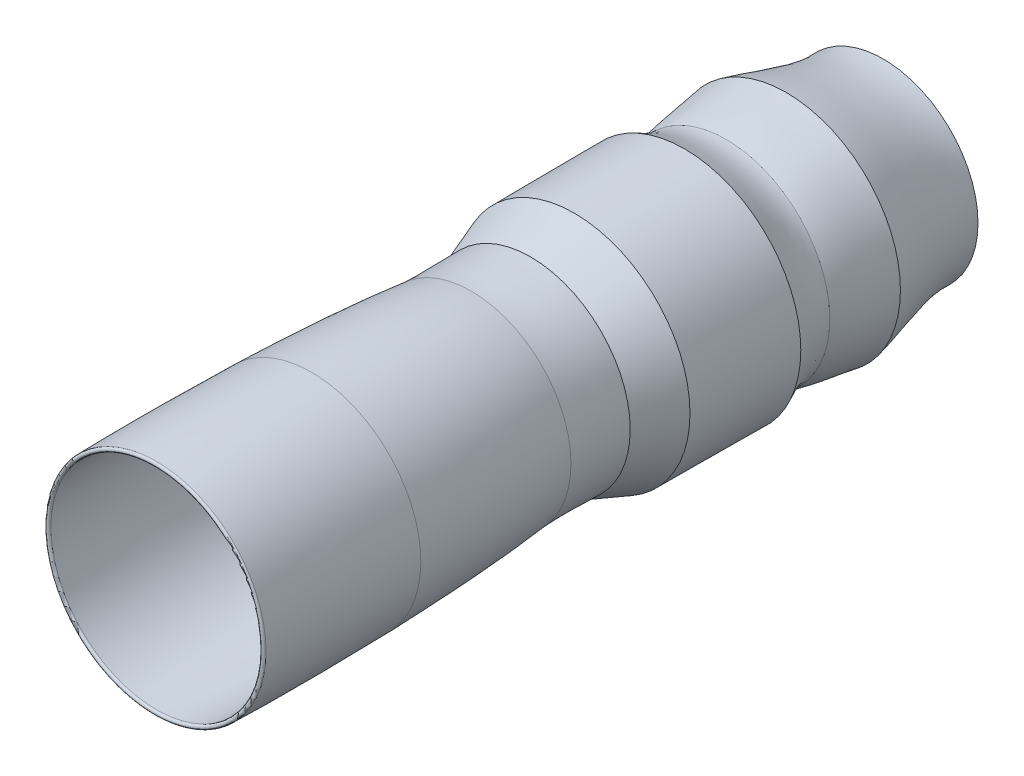
SolidWorks part; units mm, degrees
ref_plane "Front Plane" through (0, 0, 0) normal (0, 0, 1) x (1, 0, 0)
ref_plane "Top Plane" through (0, 0, 0) normal (0, 1, 0) x (1, 0, 0)
ref_plane "Right Plane" through (0, 0, 0) normal (1, 0, 0) x (0, 0, -1)
sketch "Sketch8" plane through (0, 0, 0) normal (1, 0, 0) x (0, 0, -1)
  line L0 (0, 0) -> (5590, 0) construction
  line L1 (0, 0) -> (5607.581, 0)
  line L2 (375.2101, 261.6749) -> (557.709, 261.6749)
  line L3 (557.709, 261.6749) -> (557.709, 0)
  line L4 (557.709, 0) -> (0, 0)
  spline S0 degree 2 poles (0, 0) (27.9707, 205.406) (375.2101, 261.6749) knots 0 0 0 1 1 1
  dimension "D1" = 5590
sketch "Sketch9" plane through (0, 0, 0) normal (1, 0, 0) x (0, 0, -1)
  line L0 (0, 0) -> (5607.581, 0) construction
  line L1 (557.709, 261.6749) -> (557.709, 0) construction
  line L2 (375.2101, 261.6749) -> (557.709, 261.6749) construction
  line L3 (0, 0) -> (5607.581, 0)
  line L4 (557.709, 261.6749) -> (557.709, 0)
  line L5 (375.2101, 261.6749) -> (557.709, 261.6749)
  line L6 (557.709, 0) -> (0, 0)
  parabola Q0 (0, 0) -> (375.2101, 261.6749) focus (120.2694, 20.1897) apex (19.5309, 67.2468) construction
  parabola Q1 (0, 0) -> (375.2101, 261.6749) focus (120.2694, 20.1897) apex (19.5309, 67.2468)
  point P7 (466.4596, 0)
  dimension "D1" = 261.6749
  dimension "D2" = 182.4989
sketch "Sketch11" plane through (0, 0, 0) normal (1, 0, 0) x (0, 0, -1)
  line L0 (557.709, 231.1749) -> (607.709, 231.1749)
  line L1 (557.709, 261.6749) -> (557.709, 0) construction
  line L2 (607.709, 231.1749) -> (607.709, 0)
  line L3 (0, 0) -> (5607.581, 0) construction
  line L5 (375.2101, 261.6749) -> (557.709, 261.6749) construction
  line L7 (607.709, 0) -> (557.709, 0)
  line L8 (557.709, 231.1749) -> (557.709, 0)
  dimension "D2" = 30.5
sketch "Sketch57" plane through (0, 0, 0) normal (1, 0, 0) x (0, 0, -1)
  line L1 (5548.1816, 676.7722) -> (5549.9439, 646.824)
  arc A1 (355.6183, 783.4894) -> (356.1612, 753.4943) centre (355.8897, 768.4918) ccw
  spline S0 degree 3 poles (356.1612, 753.4943) (725.1108, 760.1721) (1094.102, 758.4341) (1463.1876, 750.663) knots 0 0 0 0 1 1 1 1
  spline S1 degree 3 poles (1463.1876, 750.663) (1843.519, 737.2017) (2224.4299, 724.6791) (2602.8221, 681.8746) knots 0 0 0 0 1 1 1 1
  spline S2 degree 3 poles (2602.8221, 681.8746) (2746.451, 673.1497) (2890.1052, 679.394) (3034.5032, 681.7486) knots 0 0 0 0 1 1 1 1
  spline S3 degree 1 poles (3034.5032, 681.7486) (3347.188, 795.7739) knots 0 0 1 1
  spline S4 degree 1 poles (3347.188, 795.7739) (4122.347, 800.0453) knots 0 0 1 1
  spline S5 degree 3 poles (4122.347, 800.0453) (4218.8819, 754.2521) (4321.2413, 701.1376) (4430.393, 711.435) knots 0 0 0 0 1 1 1 1
  spline S6 degree 3 poles (4430.393, 711.435) (4568.687, 749.5665) (4711.6907, 760.5752) (4854.4305, 784.957) knots 0 0 0 0 1 1 1 1
  spline S7 degree 3 poles (4854.4305, 784.957) (5084.739, 731.7888) (5313.7621, 632.9255) (5549.9439, 646.824) knots 0 0 0 0 1 1 1 1
  spline S8 degree 1 poles (355.6183, 783.4894) (1464.034, 780.6519) knots 0 0 1 1 construction
  spline S9 degree 1 poles (1464.034, 780.6519) (2605.4158, 711.7724) knots 0 0 1 1 construction
  spline S10 degree 1 poles (2605.4158, 711.7724) (3028.9628, 711.6607) knots 0 0 1 1 construction
  spline S11 degree 1 poles (3028.9628, 711.6607) (3341.8087, 825.7447) knots 0 0 1 1 construction
  spline S12 degree 1 poles (3341.8087, 825.7447) (4129.0233, 830.0826) knots 0 0 1 1 construction
  spline S13 degree 1 poles (4129.0233, 830.0826) (4425.0429, 741.076) knots 0 0 1 1 construction
  spline S14 degree 1 poles (4425.0429, 741.076) (4855.3132, 815.5423) knots 0 0 1 1 construction
  spline S15 degree 1 poles (4855.3132, 815.5423) (5548.1816, 676.7722) knots 0 0 1 1 construction
  spline S16 degree 3 poles (355.6183, 783.4894) (447.9786, 785.1611) (632.7273, 787.4512) (909.8236, 787.9485) (1186.9212, 785.7337) (1371.672, 782.5965) (1464.034, 780.6519) knots 0 0 0 0 0.250049 0.500097 0.750146 1.000194 1.000194 1.000194 1.000194
  spline S17 degree 3 poles (1464.034, 780.6519) (1511.5656, 778.9695) (1606.6034, 775.6358) (1796.8781, 768.5929) (2034.844, 758.176) (2272.7713, 743.1606) (2439.1709, 728.9467) (2534.1886, 719.5826) (2581.6852, 714.4543) (2605.4158, 711.7724) knots -0.000188 -0.000188 -0.000188 -0.000188 0.12475 0.249688 0.499564 0.749441 0.874379 0.936848 0.999317 0.999317 0.999317 0.999317
  spline S18 degree 3 poles (2605.4158, 711.7724) (2622.8817, 710.7181) (2657.8227, 709.0567) (2727.908, 707.2414) (2798.2607, 707.2814) (2868.927, 708.3467) (2922.088, 709.4485) (2966.5344, 710.4436) (3002.1731, 711.1794) (3020.0363, 711.5097) (3028.9628, 711.6607) knots 0.001824 0.001824 0.001824 0.001824 0.125144 0.248463 0.495103 0.618422 0.741742 0.865061 0.926721 0.988381 0.988381 0.988381 0.988381
  spline S19 degree 1 poles (3028.9628, 711.6607) (3341.8087, 825.7447) knots 0.015151 0.015151 1.015666 1.015666
  spline S20 degree 1 poles (3341.8087, 825.7447) (4129.0233, 830.0826) knots -0.006726 -0.006726 1.008826 1.008826
  spline S21 degree 3 poles (4129.0233, 830.0826) (4130.5508, 829.358) (4133.6, 827.9116) (4139.7453, 824.996) (4150.5225, 819.8598) (4172.071, 809.5594) (4202.9003, 794.9992) (4239.956, 778.621) (4277.0445, 764.15) (4314.1118, 752.3685) (4344.9406, 745.4008) (4369.5689, 741.871) (4388.0328, 740.3244) (4403.4328, 740.019) (4415.7667, 740.4044) (4421.9569, 740.8154) (4425.0429, 741.076) knots -0.021345 -0.021345 -0.021345 -0.021345 -0.005521 0.010303 0.04195 0.105244 0.231833 0.358422 0.485011 0.6116 0.738189 0.801483 0.864777 0.928072 0.959719 0.991366 0.991366 0.991366 0.991366
  spline S22 degree 3 poles (4425.0429, 741.076) (4433.9674, 743.5142) (4451.9005, 748.1845) (4487.7559, 756.6949) (4532.6834, 765.9794) (4586.6498, 775.454) (4640.6175, 783.7709) (4694.5233, 791.4285) (4748.3049, 798.918) (4792.9853, 805.4248) (4824.1372, 810.3241) (4839.7145, 812.8904) (4848.559, 814.3863) (4853.0691, 815.159) (4855.3132, 815.5423) knots 0.00616 0.00616 0.00616 0.00616 0.069141 0.132123 0.258085 0.384047 0.510009 0.635971 0.761933 0.887895 0.950876 0.982367 0.998112 1.013857 1.013857 1.013857 1.013857
  spline S23 degree 3 poles (4855.3132, 815.5423) (4857.1278, 815.1234) (4860.7332, 814.2922) (4868.1335, 812.5766) (4881.0086, 809.5262) (4899.4061, 805.0109) (4921.4239, 799.381) (4950.7293, 791.6298) (4987.2585, 781.56) (5045.5132, 764.9587) (5118.0073, 743.8919) (5233.4411, 712.0406) (5348.1828, 686.7296) (5448.205, 676.6035) (5498.1875, 675.2942) (5526.7469, 675.725) (5541.0435, 676.3521) (5548.1816, 676.7722) knots -0.008489 -0.008489 -0.008489 -0.008489 -0.000611 0.007268 0.023026 0.054541 0.086056 0.117572 0.180602 0.243633 0.369694 0.495755 0.747878 0.873939 0.936969 0.968485 1 1 1 1
  dimension "D1" = 30
revolve "Revolve8" add sketch "Sketch57" angle 360 about L1
